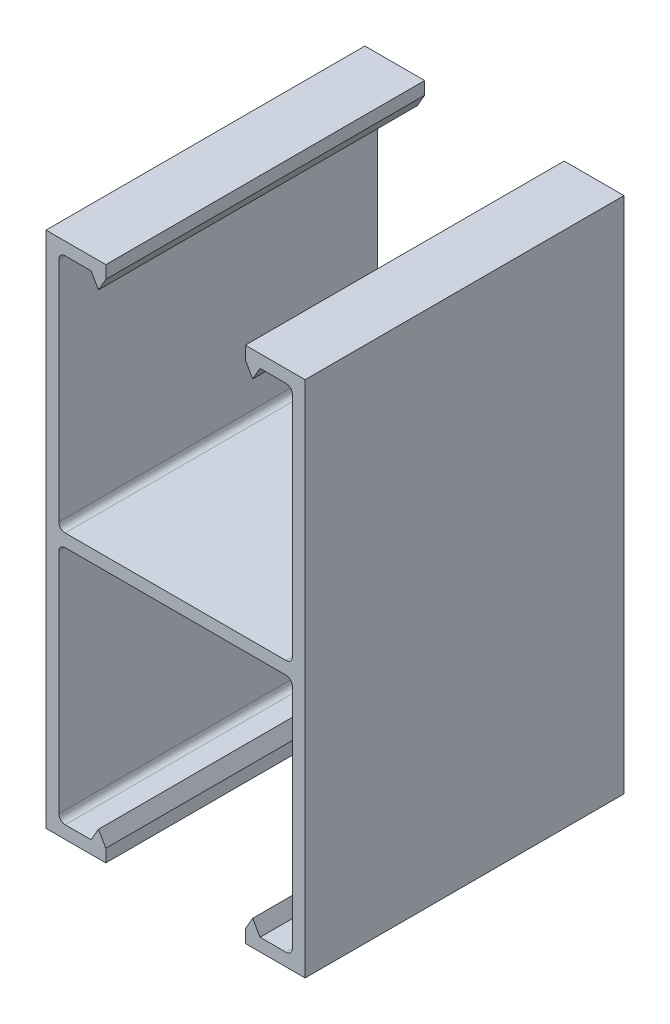
SolidWorks part; units mm, degrees
ref_plane "Plane1" through (0, 0, 0) normal (0, 0, 1) x (1, 0, 0)
ref_plane "Plane2" through (0, 0, 0) normal (0, 1, 0) x (1, 0, 0)
ref_plane "Plane3" through (0, 0, 0) normal (1, 0, 0) x (0, 0, -1)
sketch "Sketch1" plane through (0, 0, 0) normal (0, 0, 1) x (1, 0, 0)
  line L0 (-5.5563, 20.6375) -> (-10.3188, 20.6375)
  line L1 (-10.3188, 20.6375) -> (-10.3187, -20.6375)
  line L2 (-6.7294, -19.6215) -> (-8.7947, -19.6215)
  line L3 (10.3188, -20.6375) -> (10.3187, 20.6375)
  line L4 (10.3187, 20.6375) -> (5.5562, 20.6375)
  line L5 (8.7948, 19.6215) -> (6.7294, 19.6215)
  line L6 (9.3028, 1.016) -> (9.3028, 19.1135)
  line L7 (-8.7947, 0.508) -> (8.7948, 0.508)
  line L8 (-9.3028, 19.1135) -> (-9.3027, 1.016)
  line L9 (-6.7294, 19.6215) -> (-8.7948, 19.6215)
  line L10 (6.7294, 19.6215) -> (6.1428, 18.6055)
  line L11 (6.1428, 18.6055) -> (5.5562, 19.6215)
  line L12 (5.5562, 19.6215) -> (5.5562, 20.6375)
  line L13 (-6.7294, 19.6215) -> (-6.1428, 18.6055)
  line L14 (-6.1428, 18.6055) -> (-5.5563, 19.6215)
  line L15 (-5.5563, 19.6215) -> (-5.5563, 20.6375)
  line L16 (22.86, 0) -> (-25.4, 0) construction
  line L17 (6.1428, -18.6055) -> (5.5562, -19.6215)
  line L18 (6.7294, -19.6215) -> (6.1428, -18.6055)
  line L19 (8.7948, -19.6215) -> (6.7294, -19.6215)
  line L20 (10.3188, -20.6375) -> (5.5562, -20.6375)
  line L21 (5.5562, -19.6215) -> (5.5562, -20.6375)
  line L22 (-5.5562, -20.6375) -> (-10.3187, -20.6375)
  line L23 (-5.5562, -19.6215) -> (-5.5562, -20.6375)
  line L24 (-6.1428, -18.6055) -> (-5.5562, -19.6215)
  line L25 (-6.7294, -19.6215) -> (-6.1428, -18.6055)
  line L26 (-9.3027, -19.1135) -> (-9.3027, -1.016)
  line L27 (9.3028, -1.016) -> (9.3028, -19.1135)
  line L28 (-8.7947, -0.508) -> (8.7948, -0.508)
  arc A0 (-9.3027, 1.016) -> (-8.7947, 0.508) centre (-8.7947, 1.016) ccw
  arc A1 (-8.7948, 19.6215) -> (-9.3028, 19.1135) centre (-8.7948, 19.1135) ccw
  arc A2 (9.3028, 19.1135) -> (8.7948, 19.6215) centre (8.7948, 19.1135) ccw
  arc A3 (8.7948, 0.508) -> (9.3028, 1.016) centre (8.7948, 1.016) ccw
  arc A4 (9.3028, -19.1135) -> (8.7948, -19.6215) centre (8.7948, -19.1135) cw
  arc A5 (-8.7947, -19.6215) -> (-9.3027, -19.1135) centre (-8.7947, -19.1135) cw
  arc A6 (8.7948, -0.508) -> (9.3028, -1.016) centre (8.7948, -1.016) cw
  arc A7 (-9.3027, -1.016) -> (-8.7947, -0.508) centre (-8.7947, -1.016) cw
  dimension "D5" = 0.508
  dimension "Width" = 20.6375
  dimension "D8" = 10.3187
  dimension "D10" = 11.1125
  dimension "edge" = 4.7625
  dimension "D13" = 0.5866
  dimension "Height" = 41.275
  dimension "D3" = 20.6375
  dimension "D4" = 60
extrude "Base-Extrude" add sketch "Sketch1" along normal mid plane 25.4
equation "\"D8@Sketch1\" = \"Width@Sketch1\" / 2"
equation "\"D10@Sketch1\" = \"Width@Sketch1\" - 2 * \"edge@Sketch1\""
equation "\"D5@Sketch1\" = \"gauge@Sketch1\" / 2"
equation "\"D3@Sketch1\" = \"Height@Sketch1\" / 2"
equation "\"D13@Sketch1\" = \"gauge@Sketch1\" * .577350269"
